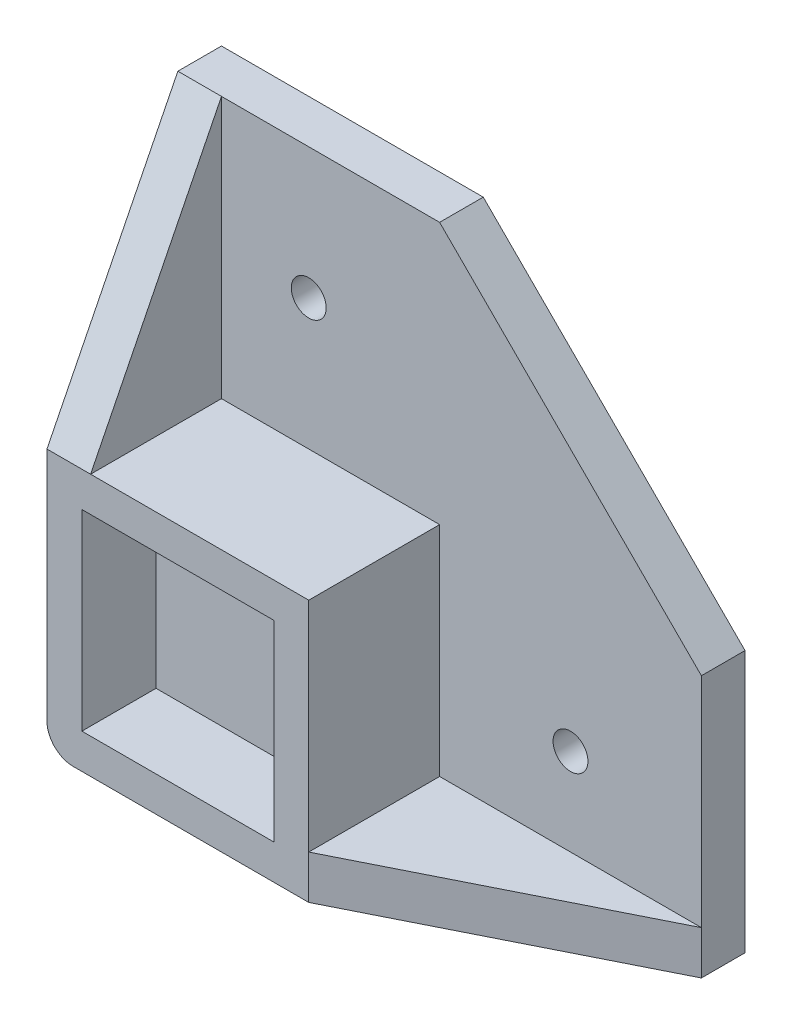
SolidWorks part; units mm, degrees
ref_plane "Płaszczyzna przednia" through (0, 0, 0) normal (0, 0, 1) x (1, 0, 0)
ref_plane "Płaszczyzna górna" through (0, 0, 0) normal (0, 1, 0) x (1, 0, 0)
ref_plane "Płaszczyzna prawa" through (0, 0, 0) normal (1, 0, 0) x (0, 0, -1)
sketch "Szkic1" plane through (0, 0, 0) normal (0, 0, 1) x (1, 0, 0)
  line L0 (0, 0) -> (0, 60)
  line L1 (0, 60) -> (30, 60)
  line L2 (30, 60) -> (60, 30)
  line L3 (60, 30) -> (60, 0)
  line L4 (60, 0) -> (0, 0)
  point P3 (0, 0)
  point P7 (0, 0)
  point P8 (0, 0)
extrude "Dodanie-wyciągnięcie1" add sketch "Szkic1" along normal blind 5
sketch "Szkic2" plane through (0, 0, 0) normal (0, 0, -1) x (-1, 0, 0)
  circle A0 centre (-45, 15) radius 2
  circle A1 centre (-15, 45) radius 2
  point P4 (0, 0)
extrude "Wytnij-wyciągnięcie1" cut sketch "Szkic2" against normal up to next
sketch "Szkic3" plane through (0, 0, 5) normal (0, 0, 1) x (1, 0, 0)
  line L1 (0, 0) -> (30, 0)
  line L2 (0, 0) -> (0, 30)
  line L3 (0, 30) -> (30, 30)
  line L4 (30, 0) -> (30, 30)
  point P5 (0, 0)
extrude "Dodanie-wyciągnięcie2" add sketch "Szkic3" along normal blind 15
sketch "Szkic4" plane through (0, 0, 0) normal (0, -1, 0) x (-1, 0, 0)
  line L0 (-30, -5) -> (-30, -20)
  line L1 (-30, -20) -> (-60, -5)
  line L2 (-60, -5) -> (-30, -5)
extrude "Dodanie-wyciągnięcie3" add sketch "Szkic4" against normal blind 5
sketch "Szkic5" plane through (0, 0, 0) normal (-1, 0, 0) x (0, 0, 1)
  line L0 (5, 30) -> (20, 30)
  line L1 (20, 30) -> (5, 60)
  line L2 (5, 60) -> (5, 30)
extrude "Dodanie-wyciągnięcie4" add sketch "Szkic5" against normal blind 5
fillet "Zaokrąglenie1" radius 3 1 edges at (0, 0, 10)
sketch "Szkic6" plane through (0, 0, 20) normal (0, 0, 1) x (1, 0, 0)
  line L1 (26, 26) -> (4, 26)
  line L2 (26, 26) -> (26, 4)
  line L3 (26, 4) -> (4, 4)
  line L4 (4, 26) -> (4, 4)
  point P4 (0, 0)
  point P5 (0, 0)
  point P6 (0, 0)
extrude "Wytnij-wyciągnięcie2" cut sketch "Szkic6" against normal blind 8.5
